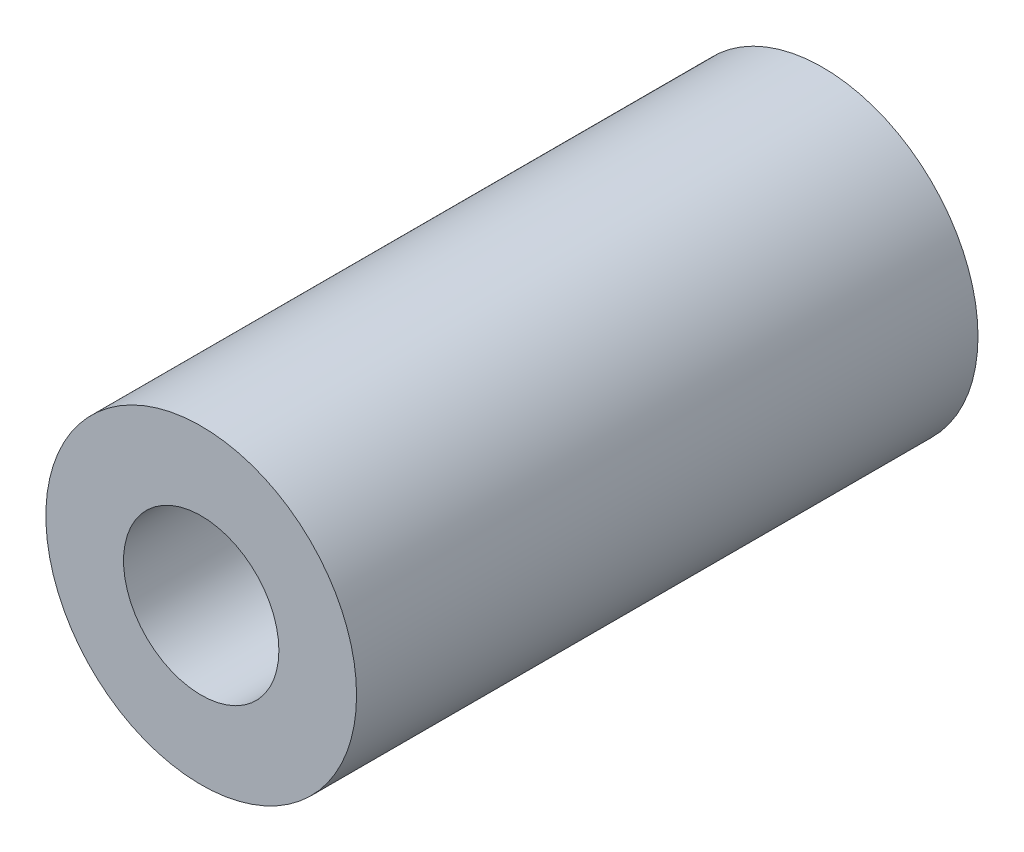
SolidWorks part; units mm, degrees
ref_plane "前视基准面" through (0, 0, 0) normal (0, 0, 1) x (1, 0, 0)
ref_plane "上视基准面" through (0, 0, 0) normal (0, 1, 0) x (1, 0, 0)
ref_plane "右视基准面" through (0, 0, 0) normal (1, 0, 0) x (0, 0, -1)
other "Configuration Table"
sketch "草图1" plane through (0, 0, 0) normal (0, 0, 1) x (1, 0, 0)
  circle A0 centre (0, 0) radius 1.5
  circle A1 centre (0, 0) radius 3
  dimension "D1" = 3
  dimension "D2" = 6
extrude "凸台-拉伸1" add sketch "草图1" along normal blind 12
